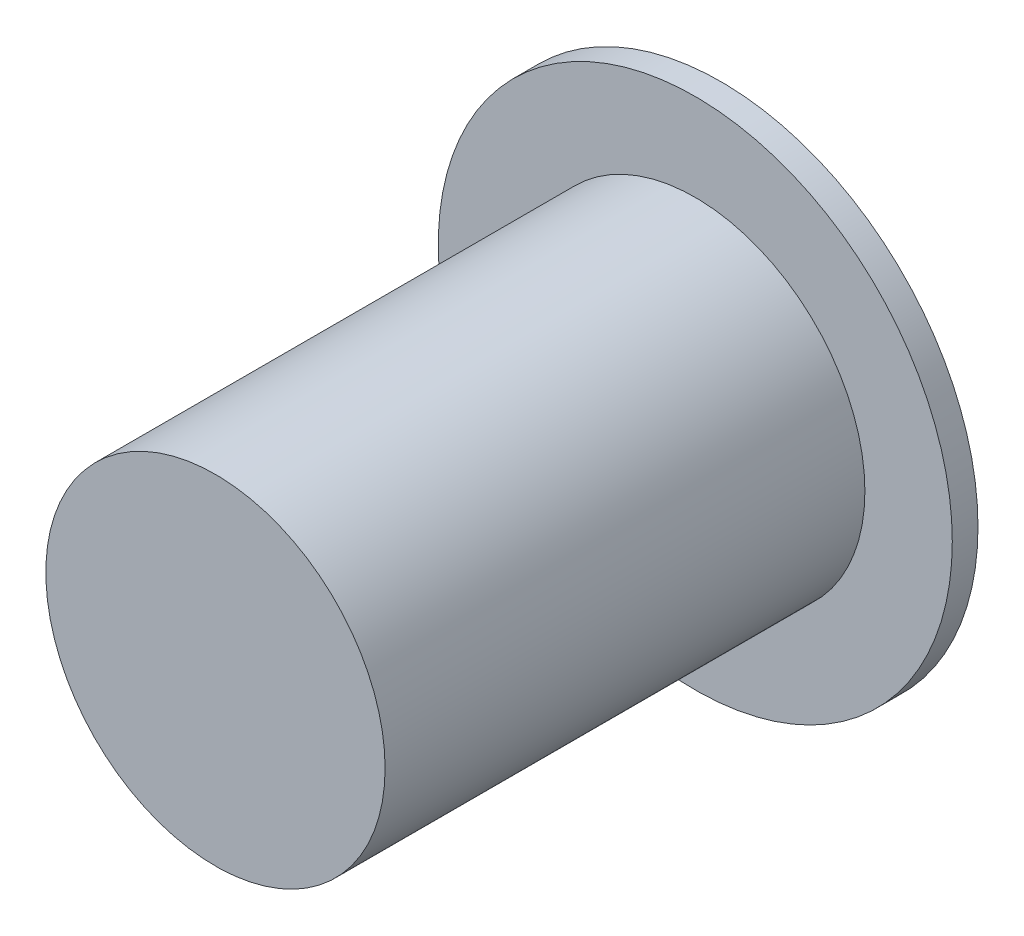
SolidWorks part; units mm, degrees
ref_plane "Front Plane" through (0, 0, 0) normal (0, 0, 1) x (1, 0, 0)
ref_plane "Top Plane" through (0, 0, 0) normal (0, 1, 0) x (1, 0, 0)
ref_plane "Right Plane" through (0, 0, 0) normal (1, 0, 0) x (0, 0, -1)
sketch "Sketch1" plane through (0, 0, 0) normal (0, 0, 1) x (1, 0, 0)
  circle A0 centre (0, 0) radius 15
extrude "Boss-Extrude1" add sketch "Sketch1" along normal blind 1.5
sketch "Sketch2" plane through (0, 0, 1.5) normal (0, 0, 1) x (1, 0, 0)
  circle A0 centre (0, 0) radius 9.9
extrude "Boss-Extrude2" add sketch "Sketch2" along normal blind 28
